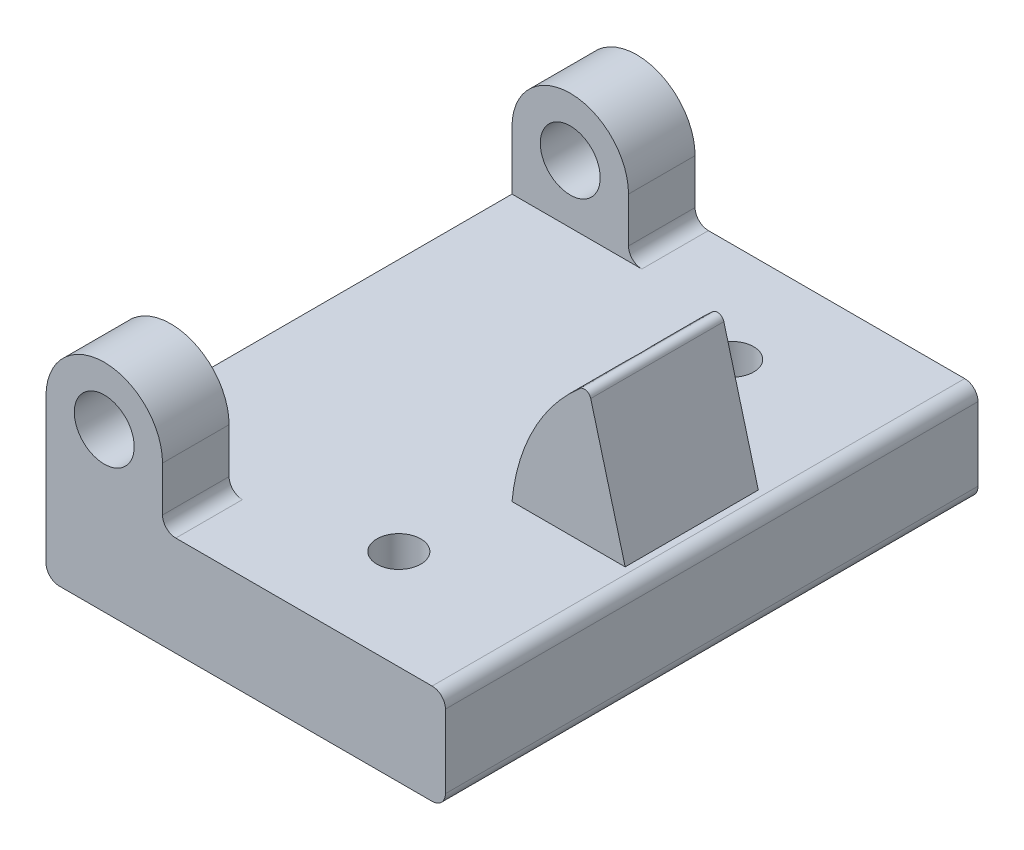
SolidWorks part; units mm, degrees
ref_plane "Front Plane" through (0, 0, 0) normal (0, 0, 1) x (1, 0, 0)
ref_plane "Top Plane" through (0, 0, 0) normal (0, 1, 0) x (1, 0, 0)
ref_plane "Right Plane" through (0, 0, 0) normal (1, 0, 0) x (0, 0, -1)
sketch "Sketch1" plane through (0, 0, 0) normal (0, 0, 1) x (1, 0, 0)
  line L0 (2, 0) -> (58, 0)
  line L1 (60, 2) -> (60, 13)
  line L2 (58, 15) -> (19.5, 15)
  line L3 (17.5, 17) -> (17.5, 23.75)
  line L4 (0, 23.75) -> (0, 2)
  arc A0 (17.5, 23.75) -> (0, 23.75) centre (8.75, 23.75) ccw
  arc A1 (0, 2) -> (2, 0) centre (2, 2) ccw
  arc A2 (58, 0) -> (60, 2) centre (58, 2) ccw
  arc A3 (60, 13) -> (58, 15) centre (58, 13) ccw
  arc A4 (19.5, 15) -> (17.5, 17) centre (19.5, 17) cw
  point P11 (0, 0)
  dimension "D3" = 8.75
  dimension "D4" = 8.75
  dimension "D5" = 2
  dimension "D1" = 15
  dimension "D2" = 60
extrude "Boss-Extrude1" add sketch "Sketch1" against normal blind 10
sketch "Sketch2" plane through (0, 0, -10) normal (0, 0, -1) x (-1, 0, 0)
  line L0 (-58, 0) -> (-2, 0)
  line L1 (-60, 2) -> (-60, 13)
  line L2 (-58, 15) -> (0, 15)
  line L3 (0, 23.75) -> (0, 2) construction
  line L4 (0, 15) -> (0, 2)
  arc A0 (-2, 0) -> (0, 2) centre (-2, 2) ccw
  arc A1 (-58, 0) -> (-60, 2) centre (-58, 2) cw
  arc A2 (-60, 13) -> (-58, 15) centre (-58, 13) cw
extrude "Boss-Extrude2" add sketch "Sketch2" along normal blind 30
ref_plane "Plane1" through (0, 0, -40) normal (0, 0, -1) x (-1, 0, 0)
mirror "Mirror2" about plane through (0, 0, -40) normal (0, 0, -1) of "Boss-Extrude2"
mirror "Mirror3" about plane through (0, 0, -40) normal (0, 0, -1) of "Boss-Extrude1"
sketch "Sketch3" plane through (0, 0, -40) normal (0, 0, -1) x (-1, 0, 0)
  line L0 (-57, 15) -> (-40, 15)
  line L1 (-58, 15) -> (-19.5, 15) construction
  line L2 (-57, 15) -> (-51.8236, 34.3185)
  line L3 (-60, 2) -> (-60, 13) construction
  arc A0 (-51.8236, 34.3185) -> (-50.2023, 34.815) centre (-50.8577, 34.0597) cw
  arc A1 (-50.2023, 34.815) -> (-40, 15) centre (-69.865, 12.1571) cw
  dimension "D2" = 1
  dimension "D4" = 30
  dimension "D1" = 75
  dimension "D3" = 20
  dimension "D5" = 3
  dimension "D6" = 17
extrude "Boss-Extrude3" add sketch "Sketch3" along normal mid plane 20
sketch "Sketch4" plane through (0, 0, 0) normal (0, 0, 1) x (1, 0, 0)
  line L0 (0, 23.75) -> (17.5, 23.75) construction
  point P4 (8.75, 23.75)
hole_wizard "M8 Clearance Hole1" positions "Sketch5" profile "Sketch6" hole size "M8" standard "ANSI Metric" end condition through all
sketch "Sketch5" plane through (0, 0, 0) normal (0, 0, 1) x (1, 0, 0)
  point P0 (8.75, 23.75)
sketch "Sketch6" plane through (8.75, 23.75, 0) normal (1, 0, 0) x (0, -1, 0)
  line L0 (0, 0) -> (0, 80)
  line L1 (0, 80) -> (4.5, 80)
  line L2 (4.5, 80) -> (4.5, 0)
  line L5 (4.5, 0) -> (0, 0)
  line L11 (0, -6.35) -> (0, 107.95) construction
  dimension "Thru Hole Dia." = 9
  dimension "Thru Hole Depth" = 80
ref_point "Point1"
ref_plane "Plane2" through (-0.5922, 33.9283, 0) normal (0.0175, -0.9998, 0) x (0, 0, 1)
sketch "Sketch7" plane through (-0.5922, 33.9283, 0) normal (0.0175, -0.9998, 0) x (0, 0, 1)
  line L0 (-50, -50.8022) -> (-30, -50.8022) construction
  line L1 (-30, -50.8022) -> (-30, -46.8022) construction
  line L2 (-50, -50.8022) -> (-50, -46.8022) construction
  line L3 (-30, -46.8022) -> (-50, -46.8022)
  point P0 (-40, -46.8022)
  dimension "D1" = 4
hole_wizard "Tap Drill for M8x1.25 Tap1" positions "Sketch9" profile "Sketch11" hole size "M8x1.25" standard "ANSI Metric"
sketch "Sketch9" plane through (-0.5922, 33.9283, 0) normal (0.0175, -0.9998, 0) x (0, 0, 1)
  point P0 (-40, -46.8022)
sketch "Sketch11" plane through (46.2029, 34.7451, -40) normal (0, 0, 1) x (-0.9998, -0.0175, 0)
  line L0 (0, 0) -> (0, 17.0429)
  line L1 (0, 17.0429) -> (3.4, 15)
  line L2 (3.4, 15) -> (3.4, 0)
  line L5 (3.4, 0) -> (0, 0)
  line L10 (0, 17.0429) -> (-3.4, 15) construction
  line L11 (0, -6.35) -> (0, 107.95) construction
  dimension "Hole Dia." = 6.8
  dimension "Hole Depth" = 15
  dimension "Drill Angle" = 118
sketch "Sketch12" plane through (0, 15, 0) normal (0, 1, 0) x (1, 0, 0)
  line L0 (58, 80) -> (58, 0) construction
  line L1 (58, 0) -> (19.5, 0) construction
  line L2 (58, 80) -> (19.5, 80) construction
  point P0 (38, 15)
  point P1 (38, 65)
  dimension "D1" = 20
  dimension "D2" = 15
  dimension "D3" = 15
hole_wizard "M6 Clearance Hole1" positions "Sketch13" profile "Sketch14" hole size "M6" standard "ANSI Metric" end condition through all
sketch "Sketch13" plane through (0, 15, 0) normal (0, 1, 0) x (1, 0, 0)
  point P0 (38, 15)
  point P3 (38, 65)
sketch "Sketch14" plane through (38, 15, -15) normal (1, 0, 0) x (0, 0, 1)
  line L0 (0, 0) -> (0, 15)
  line L1 (0, 15) -> (3.3, 15)
  line L2 (3.3, 15) -> (3.3, 0)
  line L5 (3.3, 0) -> (0, 0)
  line L11 (0, -6.35) -> (0, 107.95) construction
  dimension "Thru Hole Dia." = 6.6
  dimension "Thru Hole Depth" = 15
equation "\"lengthpedal\"= 35mm"
